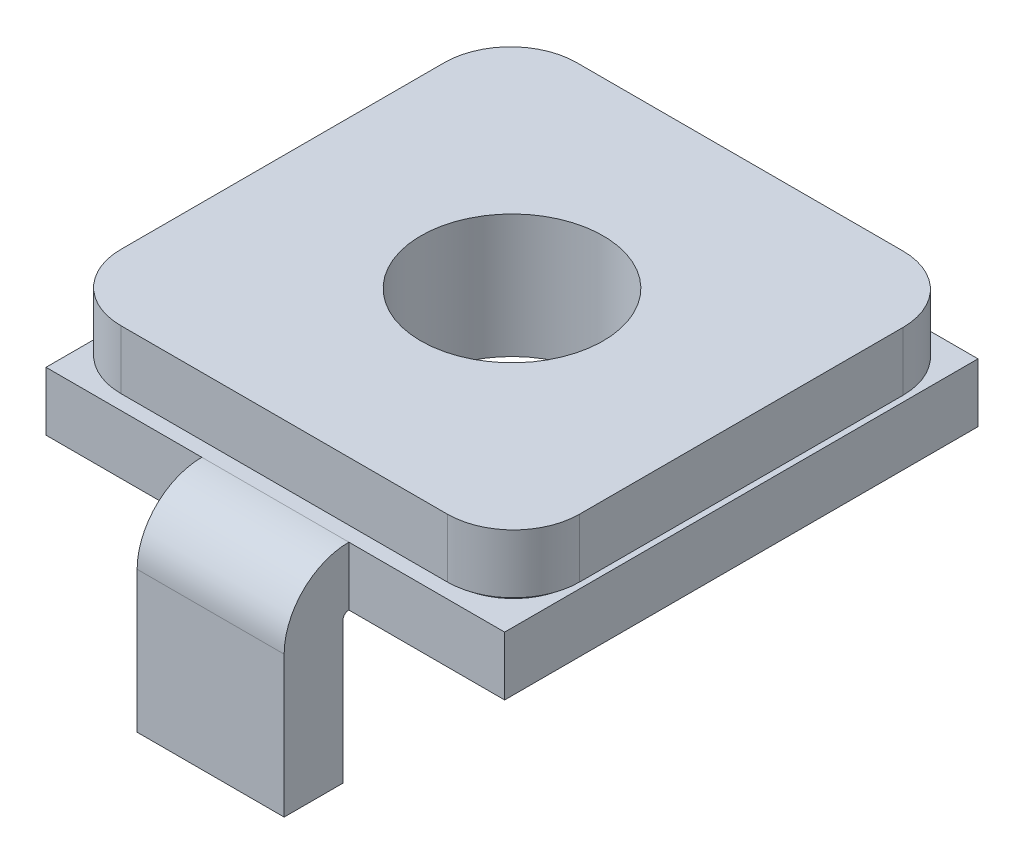
SolidWorks part; units mm, degrees
ref_plane "Front" through (0, 0, 0) normal (0, 0, 1) x (1, 0, 0)
ref_plane "Top" through (0, 0, 0) normal (0, 1, 0) x (1, 0, 0)
ref_plane "Right" through (0, 0, 0) normal (1, 0, 0) x (0, 0, -1)
sketch "Sketch1" plane through (0, 0, 0) normal (1, 0, 0) x (0, 0, -1)
  line L0 (-5.125, -3.5) -> (-5.125, -1.1)
  line L1 (-4.025, 0) -> (4.025, 0) construction
  line L2 (5.125, -1.1) -> (5.125, -3.5)
  line L3 (0, 0) -> (0, -1.7718) construction
  line L4 (-5.125, -3.5) -> (-4.125, -3.5)
  line L5 (-4.125, -3.5) -> (-4.125, -1.1)
  line L6 (-4.025, -1) -> (4.025, -1)
  line L7 (4.125, -1.1) -> (4.125, -3.5)
  line L8 (4.125, -3.5) -> (5.125, -3.5)
  line L9 (-3.75, 0) -> (-3.75, 0.1)
  line L10 (-3.75, 0.1) -> (-3.875, 0.1)
  line L11 (-3.875, 0.1) -> (-3.875, 1.1)
  line L12 (-3.875, 1.1) -> (3.875, 1.1)
  line L13 (3.875, 1.1) -> (3.875, 0.1)
  line L14 (3.875, 0.1) -> (3.75, 0.1)
  line L15 (3.75, 0.1) -> (3.75, 0)
  line L16 (-4.025, 0) -> (-3.75, 0)
  line L17 (3.75, 0) -> (4.025, 0)
  arc A0 (-5.125, -1.1) -> (-4.025, 0) centre (-4.025, -1.1) cw
  arc A1 (4.025, 0) -> (5.125, -1.1) centre (4.025, -1.1) cw
  arc A2 (-4.125, -1.1) -> (-4.025, -1) centre (-4.025, -1.1) cw
  arc A3 (4.025, -1) -> (4.125, -1.1) centre (4.025, -1.1) cw
  dimension "D2" = 1.1
  dimension "D1" = 10.25
  dimension "D3" = 3.5
  dimension "D4" = 1
  dimension "D5" = 7.5
  dimension "D6" = 0.1
  dimension "D7" = 1
  dimension "D8" = 7.75
extrude "Boss-Extrude1" add sketch "Sketch1" along normal mid plane 7.8
sketch "Sketch2" plane through (0, 0, 3.75) normal (0, 0, 1) x (1, 0, 0)
  line L0 (3.9, 0) -> (-3.9, 0) construction
  line L1 (3.9, 0.1) -> (3.775, 0.1)
  line L2 (3.9, 0.1) -> (3.9, 0)
  line L3 (3.9, 0) -> (3.775, 0)
  line L4 (3.775, 0.1) -> (3.775, 0)
  line L5 (0, 0) -> (0, 1.9403) construction
  line L6 (-3.9, 0.1) -> (-3.9, 0)
  line L7 (-3.9, 0) -> (-3.775, 0)
  line L8 (-3.775, 0.1) -> (-3.775, 0)
  line L9 (-3.9, 0.1) -> (-3.775, 0.1)
  dimension "D1" = 0.125
extrude "Cut-Extrude1" cut sketch "Sketch2" against normal through all
fillet "Fillet1" radius 1 4 edges at (3.775, 0.05, -3.75) (-3.775, 0.05, -3.75) (-3.775, 0.05, 3.75) (3.775, 0.05, 3.75)
fillet "Fillet2" radius 1.125 4 edges at (-3.9, 0.6, -3.875) (-3.9, 0.6, 3.875) (3.9, 0.6, 3.875) (3.9, 0.6, -3.875)
sketch "Sketch3" plane through (0, -3.5, 0) normal (0, -1, 0) x (1, 0, 0)
  line L1 (3.9, 5.125) -> (1.25, 5.125)
  line L2 (3.9, 5.125) -> (3.9, 4.025)
  line L3 (3.9, 4.025) -> (1.25, 4.025)
  line L4 (1.25, 5.125) -> (1.25, 4.025)
  line L5 (3.9, 4.025) -> (-3.9, 4.025) construction
  line L6 (0, 0) -> (0, 5.125) construction
  line L7 (3.9, 5.125) -> (-3.9, 5.125) construction
  line L8 (-1.25, 5.125) -> (-1.25, 4.025)
  line L9 (-3.9, 4.025) -> (-1.25, 4.025)
  line L10 (-3.9, 5.125) -> (-3.9, 4.025)
  line L11 (-3.9, 5.125) -> (-1.25, 5.125)
  dimension "D1" = 2.5
extrude "Cut-Extrude2" cut sketch "Sketch3" against normal through all
mirror "Mirror1" about plane through (0, 0, 0) normal (0, 0, 1) of "Cut-Extrude2"
sketch "Sketch4" plane through (0, 1.1, 0) normal (0, 1, 0) x (1, 0, 0)
  circle A0 centre (0, 0) radius 1.55
  dimension "D1" = 3.1
extrude "Cut-Extrude3" cut sketch "Sketch4" against normal through all
